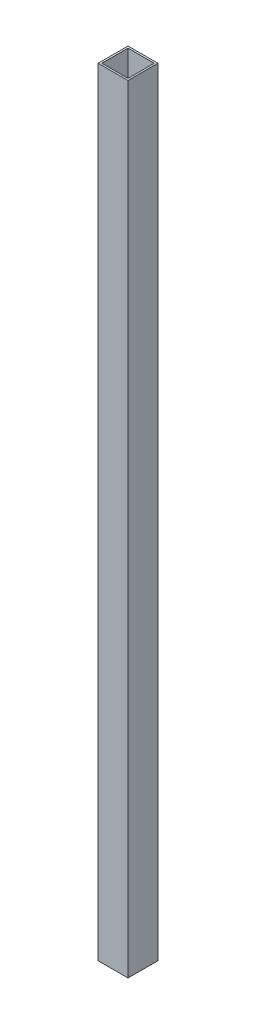
SolidWorks part; units mm, degrees
material "6061 Alloy"
ref_plane "Front Plane" through (0, 0, 0) normal (0, 0, 1) x (1, 0, 0)
ref_plane "Top Plane" through (0, 0, 0) normal (0, 1, 0) x (1, 0, 0)
ref_plane "Right Plane" through (0, 0, 0) normal (1, 0, 0) x (0, 0, -1)
sketch "Sketch1" plane through (0, 0, 0) normal (0, 1, 0) x (1, 0, 0)
  line L1 (12.7, 12.7) -> (-12.7, 12.7)
  line L2 (12.7, 12.7) -> (12.7, -12.7)
  line L3 (12.7, -12.7) -> (-12.7, -12.7)
  line L4 (-12.7, 12.7) -> (-12.7, -12.7)
  line L5 (12.7, 12.7) -> (-12.7, -12.7) construction
  line L6 (12.7, -12.7) -> (-12.7, 12.7) construction
  line L7 (11.1125, 11.1125) -> (-11.1125, 11.1125)
  line L8 (11.1125, 11.1125) -> (11.1125, -11.1125)
  line L9 (11.1125, -11.1125) -> (-11.1125, -11.1125)
  line L10 (-11.1125, 11.1125) -> (-11.1125, -11.1125)
  line L11 (11.1125, 11.1125) -> (-11.1125, -11.1125) construction
  line L12 (11.1125, -11.1125) -> (-11.1125, 11.1125) construction
  point P0 (0, 0)
  point P6 (0, 0)
  dimension "D1" = 25.4
  dimension "D2" = 25.4
  dimension "D3" = 1.5875
  dimension "D4" = 1.5875
extrude "Boss-Extrude1" add sketch "Sketch1" along normal blind 660.4
